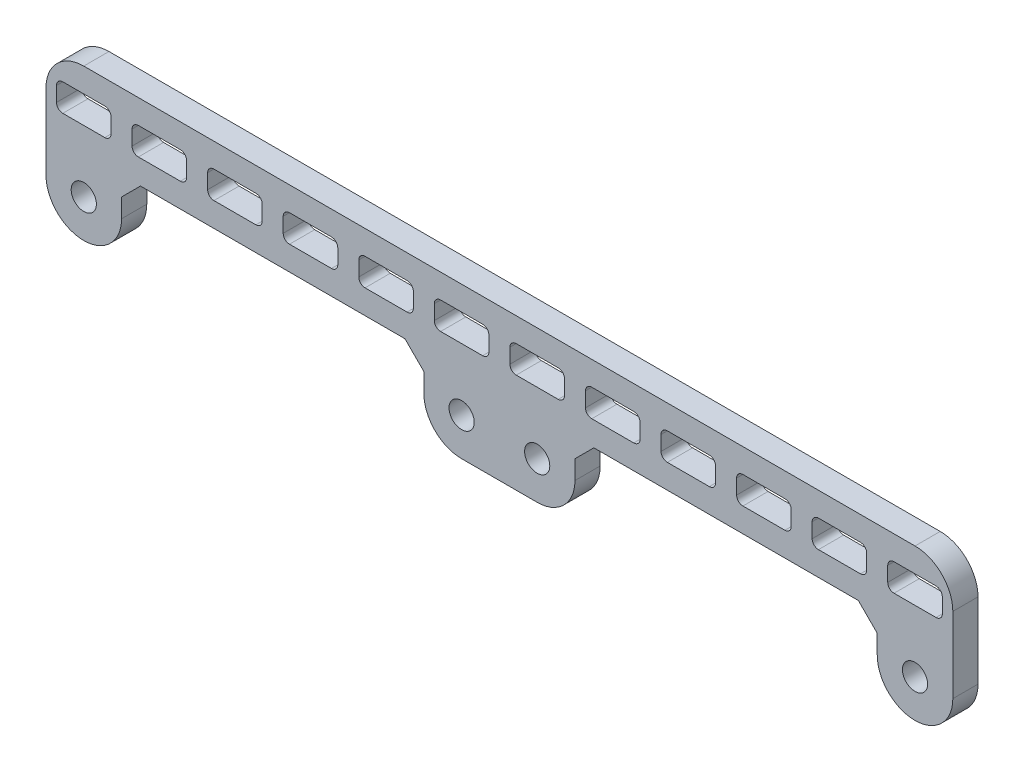
SolidWorks part; units mm, degrees
ref_plane "Alzado" through (0, 0, 0) normal (0, 0, 1) x (1, 0, 0)
ref_plane "Planta" through (0, 0, 0) normal (0, 1, 0) x (1, 0, 0)
ref_plane "Vista lateral" through (0, 0, 0) normal (1, 0, 0) x (0, 0, -1)
sketch "Model" plane through (0, 0, 0) normal (0, 0, 1) x (1, 0, 0)
  line L0 (256.4291, 228.7422) -> (355.4291, 228.7422)
  line L1 (359.9291, 224.2422) -> (359.9291, 215.2422)
  line L2 (321.9291, 222.6172) -> (316.9291, 222.6172)
  line L3 (316.1791, 223.3672) -> (316.1791, 225.1172)
  line L4 (316.9291, 225.8672) -> (321.9291, 225.8672)
  line L5 (322.6791, 225.1172) -> (322.6791, 223.3672)
  line L6 (357.9291, 222.6172) -> (352.9291, 222.6172)
  line L7 (352.1791, 223.3672) -> (352.1791, 225.1172)
  line L8 (352.9291, 225.8672) -> (357.9291, 225.8672)
  line L9 (358.6791, 225.1172) -> (358.6791, 223.3672)
  line L10 (348.9291, 222.6172) -> (343.9291, 222.6172)
  line L11 (343.1791, 223.3672) -> (343.1791, 225.1172)
  line L12 (343.9291, 225.8672) -> (348.9291, 225.8672)
  line L13 (349.6791, 225.1172) -> (349.6791, 223.3672)
  line L14 (339.9291, 222.6172) -> (334.9291, 222.6172)
  line L15 (334.1791, 223.3672) -> (334.1791, 225.1172)
  line L16 (334.9291, 225.8672) -> (339.9291, 225.8672)
  line L17 (340.6791, 225.1172) -> (340.6791, 223.3672)
  line L18 (330.9291, 222.6172) -> (325.9291, 222.6172)
  line L19 (325.1791, 223.3672) -> (325.1791, 225.1172)
  line L20 (325.9291, 225.8672) -> (330.9291, 225.8672)
  line L21 (331.6791, 225.1172) -> (331.6791, 223.3672)
  line L22 (317.1791, 219.7422) -> (348.6791, 219.7422)
  line L23 (314.9291, 215.2422) -> (314.9291, 217.4922)
  line L24 (350.9291, 215.2422) -> (350.9291, 217.4922)
  line L25 (350.9291, 217.4922) -> (348.6791, 219.7422)
  line L26 (314.9291, 217.4922) -> (317.1791, 219.7422)
  line L27 (251.9291, 224.2422) -> (251.9291, 215.2422)
  line L28 (289.9291, 222.6172) -> (294.9291, 222.6172)
  line L29 (295.6791, 223.3672) -> (295.6791, 225.1172)
  line L30 (294.9291, 225.8672) -> (289.9291, 225.8672)
  line L31 (289.1791, 225.1172) -> (289.1791, 223.3672)
  line L32 (253.9291, 222.6172) -> (258.9291, 222.6172)
  line L33 (259.6791, 223.3672) -> (259.6791, 225.1172)
  line L34 (258.9291, 225.8672) -> (253.9291, 225.8672)
  line L35 (253.1791, 225.1172) -> (253.1791, 223.3672)
  line L36 (262.9291, 222.6172) -> (267.9291, 222.6172)
  line L37 (268.6791, 223.3672) -> (268.6791, 225.1172)
  line L38 (267.9291, 225.8672) -> (262.9291, 225.8672)
  line L39 (262.1791, 225.1172) -> (262.1791, 223.3672)
  line L40 (271.9291, 222.6172) -> (276.9291, 222.6172)
  line L41 (277.6791, 223.3672) -> (277.6791, 225.1172)
  line L42 (276.9291, 225.8672) -> (271.9291, 225.8672)
  line L43 (271.1791, 225.1172) -> (271.1791, 223.3672)
  line L44 (280.9291, 222.6172) -> (285.9291, 222.6172)
  line L45 (286.6791, 223.3672) -> (286.6791, 225.1172)
  line L46 (285.9291, 225.8672) -> (280.9291, 225.8672)
  line L47 (280.1791, 225.1172) -> (280.1791, 223.3672)
  line L48 (294.6791, 219.7422) -> (263.1791, 219.7422)
  line L49 (296.9291, 215.2422) -> (296.9291, 217.4922)
  line L50 (260.9291, 215.2422) -> (260.9291, 217.4922)
  line L51 (260.9291, 217.4922) -> (263.1791, 219.7422)
  line L52 (296.9291, 217.4922) -> (294.6791, 219.7422)
  line L53 (301.4291, 210.7422) -> (310.4291, 210.7422)
  line L54 (307.9291, 222.6172) -> (312.9291, 222.6172)
  line L55 (313.6791, 223.3672) -> (313.6791, 225.1172)
  line L56 (312.9291, 225.8672) -> (307.9291, 225.8672)
  line L57 (307.1791, 225.1172) -> (307.1791, 223.3672)
  line L58 (298.9291, 222.6172) -> (303.9291, 222.6172)
  line L59 (304.6791, 223.3672) -> (304.6791, 225.1172)
  line L60 (303.9291, 225.8672) -> (298.9291, 225.8672)
  line L61 (298.1791, 225.1172) -> (298.1791, 223.3672)
  arc A0 (359.9291, 224.2422) -> (355.4291, 228.7422) centre (355.4291, 224.2422) ccw
  circle A1 centre (301.4291, 215.2422) radius 1.5
  circle A2 centre (355.4291, 215.2422) radius 1.5
  arc A3 (316.1791, 223.3672) -> (316.9291, 222.6172) centre (316.9291, 223.3672) ccw
  arc A4 (316.9291, 225.8672) -> (316.1791, 225.1172) centre (316.9291, 225.1172) ccw
  arc A5 (322.6791, 225.1172) -> (321.9291, 225.8672) centre (321.9291, 225.1172) ccw
  arc A6 (321.9291, 222.6172) -> (322.6791, 223.3672) centre (321.9291, 223.3672) ccw
  arc A7 (352.1791, 223.3672) -> (352.9291, 222.6172) centre (352.9291, 223.3672) ccw
  arc A8 (352.9291, 225.8672) -> (352.1791, 225.1172) centre (352.9291, 225.1172) ccw
  arc A9 (358.6791, 225.1172) -> (357.9291, 225.8672) centre (357.9291, 225.1172) ccw
  arc A10 (357.9291, 222.6172) -> (358.6791, 223.3672) centre (357.9291, 223.3672) ccw
  arc A11 (343.1791, 223.3672) -> (343.9291, 222.6172) centre (343.9291, 223.3672) ccw
  arc A12 (343.9291, 225.8672) -> (343.1791, 225.1172) centre (343.9291, 225.1172) ccw
  arc A13 (349.6791, 225.1172) -> (348.9291, 225.8672) centre (348.9291, 225.1172) ccw
  arc A14 (348.9291, 222.6172) -> (349.6791, 223.3672) centre (348.9291, 223.3672) ccw
  arc A15 (334.1791, 223.3672) -> (334.9291, 222.6172) centre (334.9291, 223.3672) ccw
  arc A16 (334.9291, 225.8672) -> (334.1791, 225.1172) centre (334.9291, 225.1172) ccw
  arc A17 (340.6791, 225.1172) -> (339.9291, 225.8672) centre (339.9291, 225.1172) ccw
  arc A18 (339.9291, 222.6172) -> (340.6791, 223.3672) centre (339.9291, 223.3672) ccw
  arc A19 (325.1791, 223.3672) -> (325.9291, 222.6172) centre (325.9291, 223.3672) ccw
  arc A20 (325.9291, 225.8672) -> (325.1791, 225.1172) centre (325.9291, 225.1172) ccw
  arc A21 (331.6791, 225.1172) -> (330.9291, 225.8672) centre (330.9291, 225.1172) ccw
  arc A22 (330.9291, 222.6172) -> (331.6791, 223.3672) centre (330.9291, 223.3672) ccw
  arc A23 (310.4291, 210.7422) -> (314.9291, 215.2422) centre (310.4291, 215.2422) ccw
  arc A24 (350.9291, 215.2422) -> (359.9291, 215.2422) centre (355.4291, 215.2422) ccw
  arc A25 (256.4291, 228.7422) -> (251.9291, 224.2422) centre (256.4291, 224.2422) ccw
  circle A26 centre (256.4291, 215.2422) radius 1.5
  arc A27 (294.9291, 222.6172) -> (295.6791, 223.3672) centre (294.9291, 223.3672) ccw
  arc A28 (295.6791, 225.1172) -> (294.9291, 225.8672) centre (294.9291, 225.1172) ccw
  arc A29 (289.9291, 225.8672) -> (289.1791, 225.1172) centre (289.9291, 225.1172) ccw
  arc A30 (289.1791, 223.3672) -> (289.9291, 222.6172) centre (289.9291, 223.3672) ccw
  arc A31 (258.9291, 222.6172) -> (259.6791, 223.3672) centre (258.9291, 223.3672) ccw
  arc A32 (259.6791, 225.1172) -> (258.9291, 225.8672) centre (258.9291, 225.1172) ccw
  arc A33 (253.9291, 225.8672) -> (253.1791, 225.1172) centre (253.9291, 225.1172) ccw
  arc A34 (253.1791, 223.3672) -> (253.9291, 222.6172) centre (253.9291, 223.3672) ccw
  arc A35 (267.9291, 222.6172) -> (268.6791, 223.3672) centre (267.9291, 223.3672) ccw
  arc A36 (268.6791, 225.1172) -> (267.9291, 225.8672) centre (267.9291, 225.1172) ccw
  arc A37 (262.9291, 225.8672) -> (262.1791, 225.1172) centre (262.9291, 225.1172) ccw
  arc A38 (262.1791, 223.3672) -> (262.9291, 222.6172) centre (262.9291, 223.3672) ccw
  arc A39 (276.9291, 222.6172) -> (277.6791, 223.3672) centre (276.9291, 223.3672) ccw
  arc A40 (277.6791, 225.1172) -> (276.9291, 225.8672) centre (276.9291, 225.1172) ccw
  arc A41 (271.9291, 225.8672) -> (271.1791, 225.1172) centre (271.9291, 225.1172) ccw
  arc A42 (271.1791, 223.3672) -> (271.9291, 222.6172) centre (271.9291, 223.3672) ccw
  arc A43 (285.9291, 222.6172) -> (286.6791, 223.3672) centre (285.9291, 223.3672) ccw
  arc A44 (286.6791, 225.1172) -> (285.9291, 225.8672) centre (285.9291, 225.1172) ccw
  arc A45 (280.9291, 225.8672) -> (280.1791, 225.1172) centre (280.9291, 225.1172) ccw
  arc A46 (280.1791, 223.3672) -> (280.9291, 222.6172) centre (280.9291, 223.3672) ccw
  arc A47 (296.9291, 215.2422) -> (301.4291, 210.7422) centre (301.4291, 215.2422) ccw
  arc A48 (251.9291, 215.2422) -> (260.9291, 215.2422) centre (256.4291, 215.2422) ccw
  circle A49 centre (310.4291, 215.2422) radius 1.5
  arc A50 (312.9291, 222.6172) -> (313.6791, 223.3672) centre (312.9291, 223.3672) ccw
  arc A51 (313.6791, 225.1172) -> (312.9291, 225.8672) centre (312.9291, 225.1172) ccw
  arc A52 (307.9291, 225.8672) -> (307.1791, 225.1172) centre (307.9291, 225.1172) ccw
  arc A53 (307.1791, 223.3672) -> (307.9291, 222.6172) centre (307.9291, 223.3672) ccw
  arc A54 (303.9291, 222.6172) -> (304.6791, 223.3672) centre (303.9291, 223.3672) ccw
  arc A55 (304.6791, 225.1172) -> (303.9291, 225.8672) centre (303.9291, 225.1172) ccw
  arc A56 (298.9291, 225.8672) -> (298.1791, 225.1172) centre (298.9291, 225.1172) ccw
  arc A57 (298.1791, 223.3672) -> (298.9291, 222.6172) centre (298.9291, 223.3672) ccw
extrude "Saliente-Extruir1" add sketch "Model" along normal blind 3
